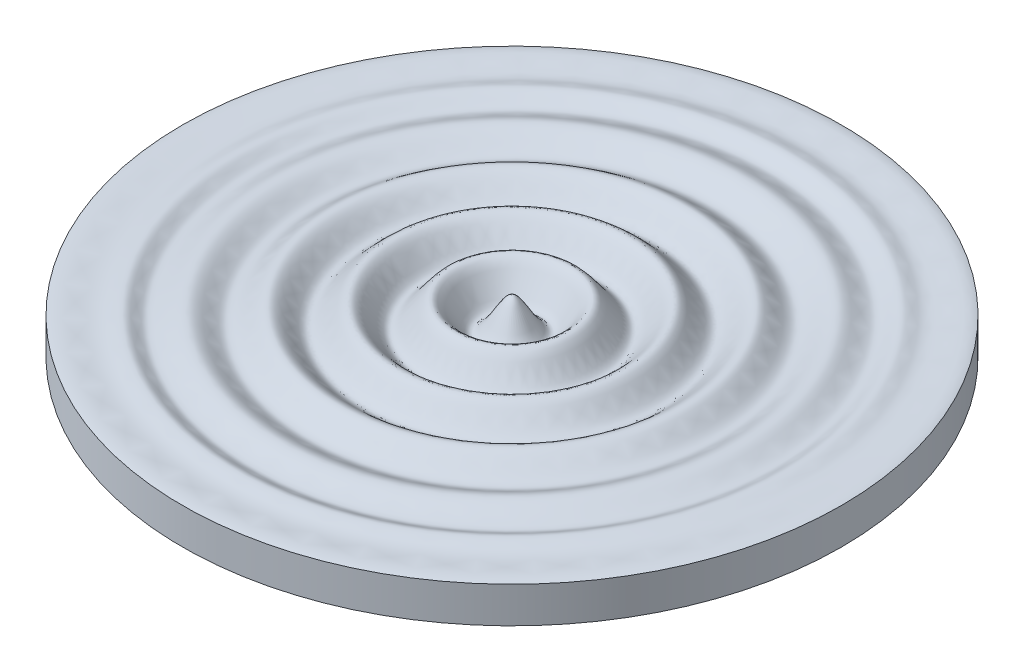
SolidWorks part; units mm, degrees
ref_plane "Plano frontal" through (0, 0, 0) normal (0, 0, 1) x (1, 0, 0)
ref_plane "Plano superior" through (0, 0, 0) normal (0, 1, 0) x (1, 0, 0)
ref_plane "Plano direito" through (0, 0, 0) normal (1, 0, 0) x (0, 0, -1)
sketch "Esboço1" plane through (0, 0, 0) normal (0, 0, 1) x (1, 0, 0)
  line L0 (-1000, 0) -> (49000, 0) construction
  line L1 (0, -1000) -> (0, 49000) construction
  line L2 (-457.0495, 0) -> (-457.0495, -50)
  line L3 (-457.0495, -50) -> (0, -50)
  line L4 (-20, 23.0876) -> (-20, -23.0876) construction
  line L5 (-39.9887, 22.0317) -> (-39.9887, -22.0317) construction
  line L6 (-59.9773, 20.9758) -> (-59.9773, -22.2987) construction
  line L7 (-79.966, 19.9199) -> (-79.966, -22.2987) construction
  line L8 (-99.9546, 18.8639) -> (-99.9546, -22.2987) construction
  line L9 (-119.9433, 17.808) -> (-119.9433, -22.2987) construction
  line L10 (-139.9319, 16.7521) -> (-139.9319, -22.2987) construction
  line L11 (-159.9206, 15.6962) -> (-159.9206, -22.2987) construction
  line L12 (-179.9092, 14.6402) -> (-179.9092, -22.2987) construction
  line L13 (-199.8979, 13.5843) -> (-199.8979, -22.2987) construction
  line L14 (-219.8865, 12.5284) -> (-219.8865, -22.2987) construction
  line L15 (-239.8752, 11.4725) -> (-239.8752, -22.2987) construction
  line L16 (-259.8638, 10.4165) -> (-259.8638, -22.2987) construction
  line L17 (-279.8525, 9.3606) -> (-279.8525, -22.2987) construction
  line L18 (-299.8412, 8.3047) -> (-299.8412, -22.2987) construction
  line L19 (-319.8298, 7.2488) -> (-319.8298, -22.2987) construction
  line L20 (-339.8185, 6.1929) -> (-339.8185, -22.2987) construction
  line L21 (-359.8071, 5.1369) -> (-359.8071, -22.2987) construction
  line L22 (-379.7958, 4.081) -> (-379.7958, -22.2987) construction
  line L23 (-399.7844, 3.0251) -> (-399.7844, -21.335) construction
  line L24 (0, -50) -> (0, 24.1441)
  line L25 (-457.0495, 0) -> (0, 24.1441) construction
  line L26 (-457.0495, 0) -> (0, -24.1441) construction
  spline S0 degree 3 poles (0, 24.1441) (-12.2097, 24.0039) (-33.2667, -44.817) (-59.2857, -0.1772) (-80.1387, 29.901) (-99.2528, 0.0783) (-120.1173, -26.7352) (-139.2395, 0.0299) (-160.0905, 23.5694) (-179.2392, -0.1473) (-200.0599, -20.403) (-219.2549, 0.2714) (-240.0241, 17.2362) (-259.2928, -0.3997) (-279.9719, -14.0621) (-299.1296, 0.3041) (-319.4877, 10.8532) (-339.0454, 0.0622) (-360.7565, -9.8626) (-378.7773, 8.9949) (-412.1361, -8.2719) (-437.918, 5.6098) (-457.0495, 0) knots 0 0 0 0 0.110465 0.164248 0.215268 0.266288 0.314688 0.363088 0.409037 0.454986 0.49868 0.542374 0.584042 0.625709 0.665614 0.705519 0.74235 0.782475 0.819787 0.859584 0.896468 1 1 1 1
  dimension "D1" = 457.0495
  dimension "D2" = 20
  dimension "D4" = 50
  dimension "D3" = 20
revolve "Revolução1" add sketch "Esboço1" angle 360 about L1
